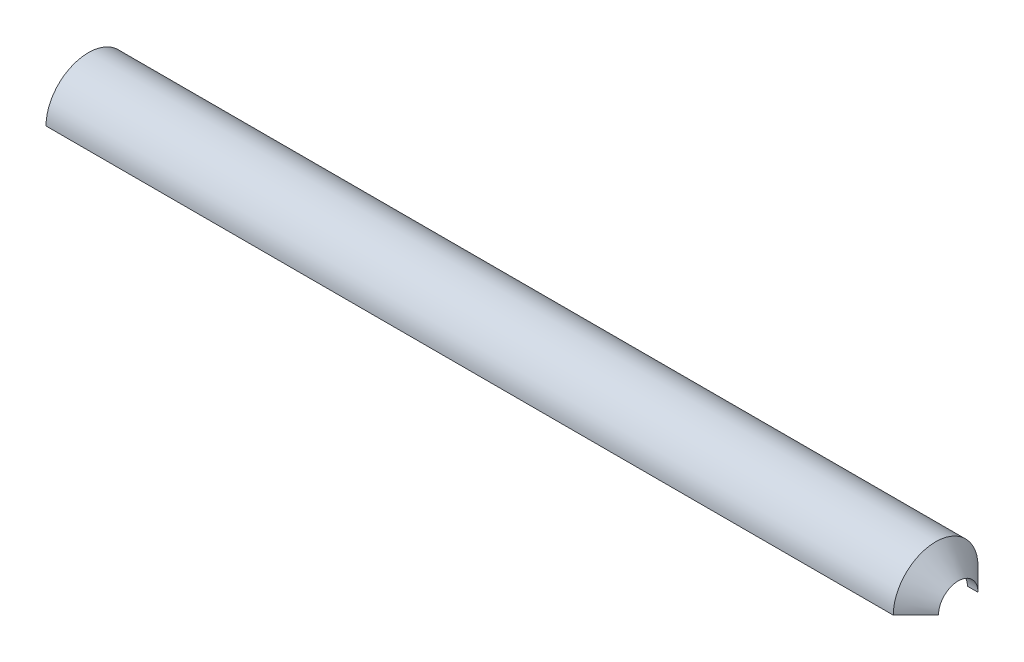
SolidWorks part; units mm, degrees
ref_plane "Front Plane" through (0, 0, 0) normal (0, 0, 1) x (1, 0, 0)
ref_plane "Top Plane" through (0, 0, 0) normal (0, 1, 0) x (1, 0, 0)
ref_plane "Right Plane" through (0, 0, 0) normal (1, 0, 0) x (0, 0, -1)
sketch "Sketch1" plane through (0, 0, 0) normal (1, 0, 0) x (0, 0, -1)
  line L0 (-6, 0) -> (-4.5, 0)
  line L1 (4.5, 0) -> (6, 0)
  arc A0 (6, 0) -> (-6, 0) centre (0, 0) ccw
  arc A1 (4.5, 0) -> (-4.5, 0) centre (0, 0) ccw
  dimension "D1" = 12
  dimension "D2" = 9
extrude "Boss-Extrude1" add sketch "Sketch1" along normal mid plane 120
sketch "Sketch2" plane through (-60, 0, 0) normal (-1, 0, 0) x (0, 0, 1)
  line L0 (-4.5, 0) -> (4.5, 0)
  arc A0 (4.5, 0) -> (-4.5, 0) centre (0, 0) ccw
extrude "Boss-Extrude2" add sketch "Sketch2" against normal blind 5
sketch "Sketch3" plane through (0, 0, 0) normal (0, -1, 0) x (1, 0, 0)
  line L0 (60, 6) -> (63.2, 2.8)
  line L1 (60, 4.5) -> (61.7, 2.8)
  line L2 (60, 6) -> (60, 4.5)
  line L3 (0, 0) -> (58.4363, 0) construction
  line L4 (60, 6) -> (-60, 6) construction
  line L6 (61.7, 2.8) -> (63.2, 2.8)
  dimension "D1" = 2.8
  dimension "D2" = 45
  dimension "D3" = 45
revolve "Revolve1" add sketch "Sketch3" angle 180 about L3
